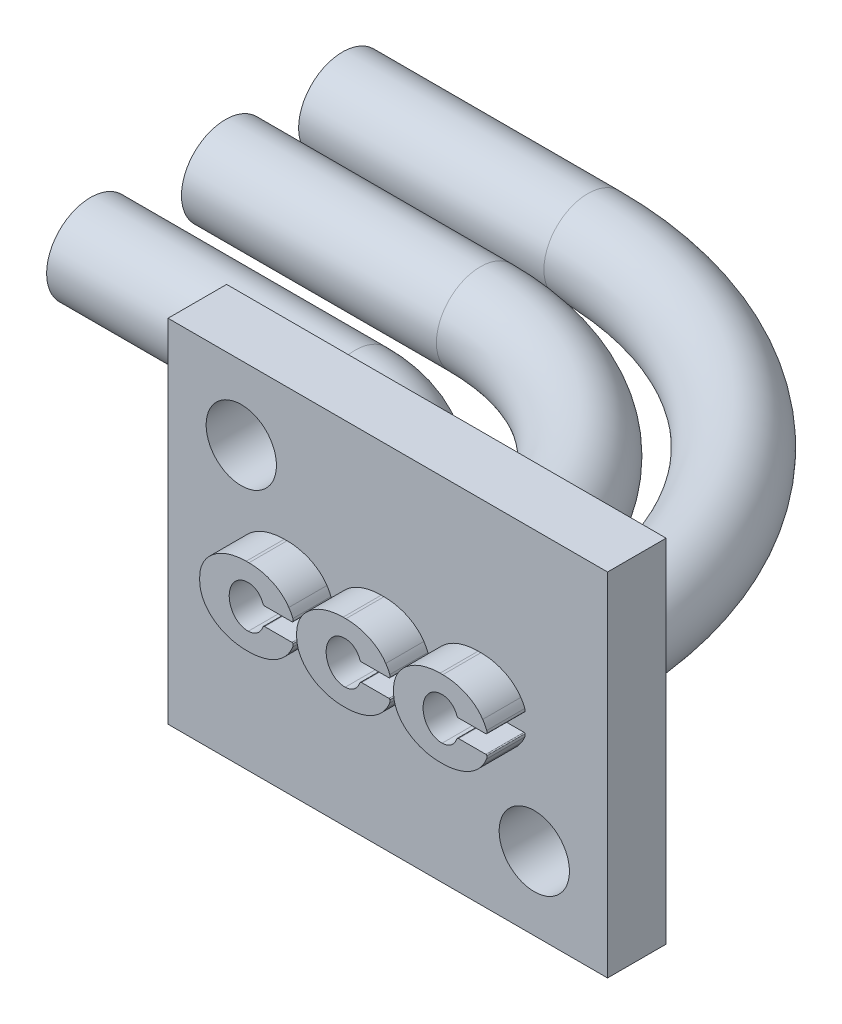
SolidWorks part; units mm, degrees
ref_plane "Front Plane" through (0, 0, 0) normal (0, 0, 1) x (1, 0, 0)
ref_plane "Top Plane" through (0, 0, 0) normal (0, 1, 0) x (1, 0, 0)
ref_plane "Right Plane" through (0, 0, 0) normal (1, 0, 0) x (0, 0, -1)
sketch "Sketch1" plane through (0, 0, 0) normal (0, 0, 1) x (1, 0, 0)
  line L1 (-7.5, 6) -> (7.5, 6)
  line L2 (-7.5, 6) -> (-7.5, -6)
  line L3 (-7.5, -6) -> (7.5, -6)
  line L4 (7.5, 6) -> (7.5, -6)
  line L5 (-7.5, 6) -> (7.5, -6) construction
  line L6 (-7.5, -6) -> (7.5, 6) construction
  point P0 (0, 0)
  dimension "D1" = 15
  dimension "D2" = 12
extrude "Boss-Extrude1" add sketch "Sketch1" along normal blind 2
sketch "Sketch2" plane through (0, 0, 2) normal (0, 0, 1) x (1, 0, 0)
  line L0 (0.4072, 0.4423) -> (1.3431, 0.4423)
  line L1 (-0.1301, 1.4531) -> (-0.2238, 1.4531)
  line L2 (-1.8094, 0.2019) -> (-1.8094, 0.0718)
  line L3 (-0.2238, -1.1794) -> (-0.1301, -1.1794)
  line L4 (1.3385, -0.1647) -> (0.4072, -0.1647)
  line L5 (-2.9011, 0.4423) -> (-1.9652, 0.4423)
  line L6 (-3.4384, 1.4531) -> (-3.5321, 1.4531)
  line L7 (-5.1177, 0.2019) -> (-5.1177, 0.0718)
  line L8 (-3.5321, -1.1794) -> (-3.4384, -1.1794)
  line L9 (-1.9698, -0.1647) -> (-2.9011, -0.1647)
  line L10 (3.7155, 0.4423) -> (4.6514, 0.4423)
  line L11 (3.1782, 1.4531) -> (3.0846, 1.4531)
  line L12 (1.4989, 0.2019) -> (1.4989, 0.0718)
  line L13 (3.0846, -1.1794) -> (3.1782, -1.1794)
  line L14 (4.6469, -0.1647) -> (3.7155, -0.1647)
  arc A0 (0.3456, 0.4859) -> (0.4072, 0.4423) centre (0.4072, 0.5078) ccw
  arc A1 (1.3431, 0.4423) -> (1.3723, 0.4672) centre (1.3386, 0.4772) ccw
  arc A2 (1.3723, 0.4672) -> (1.3681, 0.5547) centre (1.1917, 0.5024) ccw
  arc A3 (1.3681, 0.5547) -> (1.231, 0.812) centre (0.2861, 0.1431) ccw
  arc A4 (1.231, -0.5382) -> (1.3634, -0.2919) centre (0.2955, 0.1234) ccw
  arc A5 (1.3634, -0.2919) -> (1.3732, -0.1939) centre (1.1919, -0.2252) ccw
  arc A6 (1.3732, -0.1939) -> (1.3385, -0.1647) centre (1.3385, -0.1999) ccw
  arc A7 (0.4072, -0.1647) -> (0.3456, -0.2083) centre (0.4072, -0.2302) ccw
  arc A8 (-2.9627, 0.4859) -> (-2.9011, 0.4423) centre (-2.9011, 0.5078) ccw
  arc A9 (-1.9652, 0.4423) -> (-1.936, 0.4672) centre (-1.9697, 0.4772) ccw
  arc A10 (-1.936, 0.4672) -> (-1.9402, 0.5547) centre (-2.1166, 0.5024) ccw
  arc A11 (-1.9402, 0.5547) -> (-2.0773, 0.812) centre (-3.0222, 0.1431) ccw
  arc A12 (-2.0773, -0.5382) -> (-1.9449, -0.2919) centre (-3.0128, 0.1234) ccw
  arc A13 (-1.9449, -0.2919) -> (-1.9351, -0.1939) centre (-2.1164, -0.2252) ccw
  arc A14 (-1.9351, -0.1939) -> (-1.9698, -0.1647) centre (-1.9698, -0.1999) ccw
  arc A15 (-2.9011, -0.1647) -> (-2.9627, -0.2083) centre (-2.9011, -0.2302) ccw
  arc A16 (3.6539, 0.4859) -> (3.7155, 0.4423) centre (3.7155, 0.5078) ccw
  arc A17 (4.6514, 0.4423) -> (4.6806, 0.4672) centre (4.6469, 0.4772) ccw
  arc A18 (4.6806, 0.4672) -> (4.6764, 0.5547) centre (4.5, 0.5024) ccw
  arc A19 (4.6764, 0.5547) -> (4.5393, 0.812) centre (3.5944, 0.1431) ccw
  arc A20 (4.5393, -0.5382) -> (4.6717, -0.2919) centre (3.6038, 0.1234) ccw
  arc A21 (4.6717, -0.2919) -> (4.6815, -0.1939) centre (4.5002, -0.2252) ccw
  arc A22 (4.6815, -0.1939) -> (4.6469, -0.1647) centre (4.6469, -0.1999) ccw
  arc A23 (3.7155, -0.1647) -> (3.6539, -0.2083) centre (3.7155, -0.2302) ccw
  ellipse E0 centre (-0.1827, 0.137) end of major axis (-0.1791, -0.5801) minor radius 0.6209 (-0.2107, 0.8534) -> (-0.1509, -0.5792) ccw
  ellipse E1 centre (-0.2388, 0.137) end of major axis (0.0439, 0.8186) minor radius 0.6039 (0.3456, 0.4859) -> (-0.2107, 0.8534) ccw
  ellipse E2 centre (-0.2522, 0.1514) end of major axis (1.3906, 0.3966) minor radius 1.2925 (1.231, 0.812) -> (-0.1301, 1.4531) ccw
  ellipse E3 centre (-0.1614, 0.1527) end of major axis (-1.8063, 0.2821) minor radius 1.2979 (-0.2238, 1.4531) -> (-1.8094, 0.2019) ccw
  ellipse E4 centre (-0.1614, 0.121) end of major axis (1.4835, 0.2504) minor radius 1.2979 (-1.8094, 0.0718) -> (-0.2238, -1.1794) ccw
  ellipse E5 centre (-0.2522, 0.1223) end of major axis (-1.895, 0.3674) minor radius 1.2925 (-0.1301, -1.1794) -> (1.231, -0.5382) ccw
  ellipse E6 centre (-0.2388, 0.1406) end of major axis (0.0439, -0.541) minor radius 0.6039 (-0.1509, -0.5792) -> (0.3456, -0.2083) ccw
  ellipse E7 centre (-3.5471, 0.137) end of major axis (-3.2644, 0.8186) minor radius 0.6039 (-2.9627, 0.4859) -> (-3.519, 0.8534) ccw
  ellipse E8 centre (-3.5605, 0.1514) end of major axis (-1.9177, 0.3966) minor radius 1.2925 (-2.0773, 0.812) -> (-3.4384, 1.4531) ccw
  ellipse E9 centre (-3.4697, 0.1527) end of major axis (-5.1146, 0.2821) minor radius 1.2979 (-3.5321, 1.4531) -> (-5.1177, 0.2019) ccw
  ellipse E10 centre (-3.4697, 0.121) end of major axis (-1.8248, 0.2504) minor radius 1.2979 (-5.1177, 0.0718) -> (-3.5321, -1.1794) ccw
  ellipse E11 centre (-3.5605, 0.1223) end of major axis (-1.9177, -0.1229) minor radius 1.2925 (-3.4384, -1.1794) -> (-2.0773, -0.5382) ccw
  ellipse E12 centre (-3.5471, 0.1406) end of major axis (-3.8297, 0.8222) minor radius 0.6039 (-3.4592, -0.5792) -> (-2.9627, -0.2083) ccw
  ellipse E13 centre (-3.491, 0.137) end of major axis (-3.4946, 0.8541) minor radius 0.6209 (-3.519, 0.8534) -> (-3.4592, -0.5792) ccw
  ellipse E14 centre (3.1256, 0.137) end of major axis (3.1292, -0.5801) minor radius 0.6209 (3.0976, 0.8534) -> (3.1574, -0.5792) ccw
  ellipse E15 centre (3.0695, 0.137) end of major axis (3.3522, 0.8186) minor radius 0.6039 (3.6539, 0.4859) -> (3.0976, 0.8534) ccw
  ellipse E16 centre (3.0561, 0.1514) end of major axis (4.6989, 0.3966) minor radius 1.2925 (4.5393, 0.812) -> (3.1782, 1.4531) ccw
  ellipse E17 centre (3.1469, 0.1527) end of major axis (1.502, 0.2821) minor radius 1.2979 (3.0846, 1.4531) -> (1.4989, 0.2019) ccw
  ellipse E18 centre (3.1469, 0.121) end of major axis (4.7918, 0.2504) minor radius 1.2979 (1.4989, 0.0718) -> (3.0846, -1.1794) ccw
  ellipse E19 centre (3.0561, 0.1223) end of major axis (1.4133, 0.3674) minor radius 1.2925 (3.1782, -1.1794) -> (4.5393, -0.5382) ccw
  ellipse E20 centre (3.0695, 0.1406) end of major axis (3.3522, -0.541) minor radius 0.6039 (3.1574, -0.5792) -> (3.6539, -0.2083) ccw
extrude "Boss-Extrude2" add sketch "Sketch2" along normal blind 2
sketch "Sketch3" plane through (0, 0, 0) normal (0, 1, 0) x (1, 0, 0)
  line L0 (7.5, 0) -> (-7.5, 0) construction
  line L1 (2.7287, 0) -> (4.2287, 0)
  line L2 (2.7287, 0) -> (2.7287, 12.6)
  line L3 (-3.864, -2) -> (-3.864, 5.3789) construction
  line L4 (4.2287, 0) -> (4.2287, 14.1)
  line L5 (-4.614, 0) -> (-3.114, 0)
  line L6 (-4.614, 0) -> (-4.614, 4)
  line L7 (-0.1926, -2) -> (-0.1926, 4.6797) construction
  line L8 (-3.114, 0) -> (-3.114, 4)
  line L9 (-3.114, 4) -> (-4.614, 4)
  line L10 (-0.9426, 0) -> (0.5574, 0)
  line L13 (-0.9426, 0) -> (-0.9426, 8.6)
  line L14 (3.4787, -2) -> (3.4787, 2.787) construction
  line L15 (0.5574, 0) -> (0.5574, 10.1)
  line L16 (0.5574, 10.1) -> (-2.6426, 10.1)
  line L17 (-2.4226, 14.1) -> (4.2287, 14.1)
  line L18 (-0.9426, 8.6) -> (-2.6426, 8.6)
  line L19 (-2.6426, 10.1) -> (-2.6426, 8.6)
  line L20 (-2.4226, 14.1) -> (-2.4226, 12.6)
  line L21 (-2.4226, 12.6) -> (2.7287, 12.6)
  dimension "D1" = 1.5
  dimension "D2" = 4
  dimension "D3" = 1.5
  dimension "D4" = 1.5
  dimension "D5" = 4.6
  dimension "D6" = 1.5
  dimension "D7" = 2.5
  dimension "D8" = 1.5
  dimension "D9" = 1.7
  dimension "D10" = 3.4787
  dimension "D11" = 0.1926
  dimension "D12" = 3.864
extrude "Boss-Extrude3" add sketch "Sketch3" along normal mid plane 4
sketch "Sketch4" [suppressed] plane through (0, 2, 0) normal (0, 1, 0) x (1, 0, 0)
  line L1 (-2.4226, 10.1) -> (-2.4226, 8.6) construction
  line L2 (-2.894, 4) -> (-11.894, 4)
  line L3 (-2.894, 4) -> (-2.894, 5.5)
  line L4 (-2.894, 5.5) -> (-11.894, 5.5)
  line L5 (-11.894, 4) -> (-11.894, 5.5)
  dimension "D1" = 9
extrude "Boss-Extrude4" [suppressed] add sketch "Sketch4" against normal up to surface (4 mm away)
sketch "Sketch5" [suppressed] plane through (-2.4226, 0, 0) normal (-1, 0, 0) x (0, 0, 1)
  line L4 (-10.1, -2) -> (-8.6, -2)
  line L5 (-8.6, -2) -> (-8.6, 2)
  line L6 (-8.6, 2) -> (-10.1, 2)
  line L7 (-10.1, 2) -> (-10.1, -2)
  line L8 (-10.1, -2) -> (-8.6, -2)
  line L9 (-8.6, -2) -> (-8.6, 2)
  line L10 (-8.6, 2) -> (-10.1, 2)
  line L11 (-10.1, 2) -> (-10.1, -2)
  line L12 (-14.1, -2) -> (-12.6, -2)
  line L13 (-12.6, -2) -> (-12.6, 2)
  line L14 (-12.6, 2) -> (-14.1, 2)
  line L15 (-14.1, 2) -> (-14.1, -2)
  line L16 (-14.1, -2) -> (-12.6, -2)
  line L17 (-12.6, -2) -> (-12.6, 2)
  line L18 (-12.6, 2) -> (-14.1, 2)
  line L19 (-14.1, 2) -> (-14.1, -2)
  dimension "D1" = 0
  dimension "D2" = 0
extrude "Boss-Extrude5" [suppressed] add sketch "Sketch5" along normal up to surface (9.4714 mm away)
sketch "Sketch6" plane through (0, 0, 0) normal (0, 0, -1) x (-1, 0, 0)
  line L0 (-4.2287, 0) -> (-2.7287, 0) construction
  line L1 (-4.2287, 2) -> (-4.2287, -2) construction
  line L2 (-2.7287, 2) -> (-2.7287, -2) construction
  line L3 (-0.5574, 0) -> (0.9426, 0) construction
  line L4 (-0.5574, 2) -> (-0.5574, -2) construction
  line L5 (0.9426, 2) -> (0.9426, -2) construction
  line L6 (3.114, 0) -> (4.614, 0) construction
  line L7 (3.114, 2) -> (3.114, -2) construction
  line L8 (4.614, 2) -> (4.614, -2) construction
  circle A0 centre (-3.4787, 0) radius 1.5
  dimension "D1" = 3
sketch "Sketch7" plane through (0, 0, 0) normal (0, 0, -1) x (-1, 0, 0)
  circle A0 centre (0, 0) radius 1.5
  dimension "D1" = 3
sketch "Sketch8" plane through (0, 0, 0) normal (0, 0, -1) x (-1, 0, 0)
  line L0 (3.114, 0) -> (4.614, 0) construction
  circle A0 centre (3.864, 0) radius 1.5
  dimension "D1" = 3
sketch "Sketch9" plane through (0, 0, 0) normal (0, 1, 0) x (1, 0, 0)
  line L0 (-3.864, 0) -> (-3.864, 0.75)
  line L1 (-3.114, 0) -> (-4.614, 0) construction
  line L2 (-7.864, 4.75) -> (-16.894, 4.75)
  arc A0 (-3.864, 0.75) -> (-7.864, 4.75) centre (-7.864, 0.75) ccw
  point P7 (-3.864, 4.75)
  dimension "D3" = 4
  dimension "D1" = 4.75
  dimension "D2" = 13.03
sketch "Sketch10" plane through (0, 0, 0) normal (0, 1, 0) x (1, 0, 0)
  line L0 (-0.1926, 0) -> (-0.1926, 1.16)
  line L1 (0.5574, 0) -> (-0.9426, 0) construction
  line L2 (-8.1926, 9.16) -> (-16.894, 9.16)
  arc A0 (-0.1926, 1.16) -> (-8.1926, 9.16) centre (-8.1926, 1.16) ccw
  point P7 (-0.1926, 9.16)
  dimension "D3" = 8
  dimension "D1" = 16.7014
  dimension "D2" = 9.16
sketch "Sketch11" plane through (0, 0, 0) normal (0, 1, 0) x (1, 0, 0)
  line L0 (3.4787, 0) -> (3.4787, 1.35)
  line L1 (4.2287, 0) -> (2.7287, 0) construction
  line L2 (-8.5213, 13.35) -> (-16.894, 13.35)
  arc A0 (3.4787, 1.35) -> (-8.5213, 13.35) centre (-8.5213, 1.35) ccw
  point P7 (3.4787, 13.35)
  dimension "D3" = 12
  dimension "D1" = 13.35
  dimension "D2" = 20.3728
sketch "Sketch12" plane through (7.5, 0, 0) normal (1, 0, 0) x (0, 0, -1)
  line L1 (0, -6) -> (14.1, -6)
  line L2 (0, -6) -> (0, 2)
  line L3 (0, 2) -> (14.1, 2)
  line L4 (14.1, -6) -> (14.1, 2)
extrude "Cut-Extrude1" cut sketch "Sketch12" against normal through all
sweep "Sweep1" add profiles "Sketch8" path "Sketch9"
sweep "Sweep2" add profiles "Sketch7" path "Sketch10"
sweep "Sweep3" add profiles "Sketch6" path "Sketch11"
sketch "Sketch13" plane through (0, 0, 0) normal (0, 0, -1) x (-1, 0, 0)
  line L0 (-7.5, 6) -> (7.5, 6) construction
  line L1 (7.5, 6) -> (7.5, -6) construction
  line L2 (7.5, -6) -> (-7.5, -6) construction
  line L3 (-7.5, -6) -> (-7.5, 6) construction
  circle A0 centre (-5, -3.5) radius 1.2
  circle A1 centre (5, 3.5) radius 1.2
  dimension "D5" = 2.4
  dimension "D1" = 2.5
  dimension "D2" = 2.5
  dimension "D3" = 2.5
  dimension "D4" = 2.5
extrude "Cut-Extrude2" cut sketch "Sketch13" against normal through all
sketch "Sketch15" plane through (0, 0, 4) normal (0, 0, 1) x (1, 0, 0)
  line L0 (0.4072, 0.4423) -> (1.3431, 0.4423) construction
  line L1 (-0.1301, 1.4531) -> (-0.2238, 1.4531) construction
  line L2 (-1.8094, 0.2019) -> (-1.8094, 0.0718) construction
  line L3 (-0.2238, -1.1794) -> (-0.1301, -1.1794) construction
  line L4 (1.3385, -0.1647) -> (0.4072, -0.1647) construction
  line L5 (-2.9011, 0.4423) -> (-1.9652, 0.4423)
  line L6 (-3.4384, 1.4531) -> (-3.5321, 1.4531)
  line L7 (-5.1177, 0.2019) -> (-5.1177, 0.0718)
  line L8 (-3.5321, -1.1794) -> (-3.4384, -1.1794)
  line L9 (-1.9698, -0.1647) -> (-2.9011, -0.1647)
  line L10 (-2.9011, 0.4423) -> (-1.9652, 0.4423)
  line L11 (-3.4384, 1.4531) -> (-3.5321, 1.4531)
  line L12 (-5.1177, 0.2019) -> (-5.1177, 0.0718)
  line L13 (-3.5321, -1.1794) -> (-3.4384, -1.1794)
  line L14 (-1.9698, -0.1647) -> (-2.9011, -0.1647)
  line L15 (3.7155, 0.4423) -> (4.6514, 0.4423) construction
  line L16 (3.1782, 1.4531) -> (3.0846, 1.4531) construction
  line L17 (1.4989, 0.2019) -> (1.4989, 0.0718) construction
  line L18 (3.0846, -1.1794) -> (3.1782, -1.1794) construction
  line L19 (4.6469, -0.1647) -> (3.7155, -0.1647) construction
  line L20 (0.4072, 0.4423) -> (1.3431, 0.4423)
  line L21 (-0.1301, 1.4531) -> (-0.2238, 1.4531)
  line L22 (-1.8094, 0.2019) -> (-1.8094, 0.0718)
  line L23 (-0.2238, -1.1794) -> (-0.1301, -1.1794)
  line L24 (1.3385, -0.1647) -> (0.4072, -0.1647)
  line L25 (3.7155, 0.4423) -> (4.6514, 0.4423)
  line L26 (3.1782, 1.4531) -> (3.0846, 1.4531)
  line L27 (1.4989, 0.2019) -> (1.4989, 0.0718)
  line L28 (3.0846, -1.1794) -> (3.1782, -1.1794)
  line L29 (4.6469, -0.1647) -> (3.7155, -0.1647)
  arc A0 (0.3456, 0.4859) -> (0.4072, 0.4423) centre (0.4072, 0.5078) ccw construction
  arc A1 (1.3431, 0.4423) -> (1.3723, 0.4672) centre (1.3386, 0.4772) ccw construction
  arc A2 (1.3723, 0.4672) -> (1.3681, 0.5547) centre (1.1917, 0.5024) ccw construction
  arc A3 (1.3681, 0.5547) -> (1.231, 0.812) centre (0.2861, 0.1431) ccw construction
  arc A4 (1.231, -0.5382) -> (1.3634, -0.2919) centre (0.2955, 0.1234) ccw construction
  arc A5 (1.3634, -0.2919) -> (1.3732, -0.1939) centre (1.1919, -0.2252) ccw construction
  arc A6 (1.3732, -0.1939) -> (1.3385, -0.1647) centre (1.3385, -0.1999) ccw construction
  arc A7 (0.4072, -0.1647) -> (0.3456, -0.2083) centre (0.4072, -0.2302) ccw construction
  arc A8 (-2.9627, 0.4859) -> (-2.9011, 0.4423) centre (-2.9011, 0.5078) ccw
  arc A9 (-1.9652, 0.4423) -> (-1.936, 0.4672) centre (-1.9697, 0.4772) ccw
  arc A10 (-1.936, 0.4672) -> (-1.9402, 0.5547) centre (-2.1166, 0.5024) ccw
  arc A11 (-1.9402, 0.5547) -> (-2.0773, 0.812) centre (-3.0222, 0.1431) ccw
  arc A12 (-2.0773, -0.5382) -> (-1.9449, -0.2919) centre (-3.0128, 0.1234) ccw
  arc A13 (-1.9449, -0.2919) -> (-1.9351, -0.1939) centre (-2.1164, -0.2252) ccw
  arc A14 (-1.9351, -0.1939) -> (-1.9698, -0.1647) centre (-1.9698, -0.1999) ccw
  arc A15 (-2.9011, -0.1647) -> (-2.9627, -0.2083) centre (-2.9011, -0.2302) ccw
  arc A16 (-2.9627, 0.4859) -> (-2.9011, 0.4423) centre (-2.9011, 0.5078) ccw
  arc A17 (-1.9652, 0.4423) -> (-1.936, 0.4672) centre (-1.9697, 0.4772) ccw
  arc A18 (-1.936, 0.4672) -> (-1.9402, 0.5547) centre (-2.1166, 0.5024) ccw
  arc A19 (-1.9402, 0.5547) -> (-2.0773, 0.812) centre (-3.0222, 0.1431) ccw
  arc A20 (-2.0773, -0.5382) -> (-1.9449, -0.2919) centre (-3.0128, 0.1234) ccw
  arc A21 (-1.9449, -0.2919) -> (-1.9351, -0.1939) centre (-2.1164, -0.2252) ccw
  arc A22 (-1.9351, -0.1939) -> (-1.9698, -0.1647) centre (-1.9698, -0.1999) ccw
  arc A23 (-2.9011, -0.1647) -> (-2.9627, -0.2083) centre (-2.9011, -0.2302) ccw
  arc A24 (3.6539, 0.4859) -> (3.7155, 0.4423) centre (3.7155, 0.5078) ccw construction
  arc A25 (4.6514, 0.4423) -> (4.6806, 0.4672) centre (4.6469, 0.4772) ccw construction
  arc A26 (4.6806, 0.4672) -> (4.6764, 0.5547) centre (4.5, 0.5024) ccw construction
  arc A27 (4.6764, 0.5547) -> (4.5393, 0.812) centre (3.5944, 0.1431) ccw construction
  arc A28 (4.5393, -0.5382) -> (4.6717, -0.2919) centre (3.6038, 0.1234) ccw construction
  arc A29 (4.6717, -0.2919) -> (4.6815, -0.1939) centre (4.5002, -0.2252) ccw construction
  arc A30 (4.6815, -0.1939) -> (4.6469, -0.1647) centre (4.6469, -0.1999) ccw construction
  arc A31 (3.7155, -0.1647) -> (3.6539, -0.2083) centre (3.7155, -0.2302) ccw construction
  arc A32 (0.3456, 0.4859) -> (0.4072, 0.4423) centre (0.4072, 0.5078) ccw
  arc A33 (1.3431, 0.4423) -> (1.3723, 0.4672) centre (1.3386, 0.4772) ccw
  arc A34 (1.3723, 0.4672) -> (1.3681, 0.5547) centre (1.1917, 0.5024) ccw
  arc A35 (1.3681, 0.5547) -> (1.231, 0.812) centre (0.2861, 0.1431) ccw
  arc A36 (1.231, -0.5382) -> (1.3634, -0.2919) centre (0.2955, 0.1234) ccw
  arc A37 (1.3634, -0.2919) -> (1.3732, -0.1939) centre (1.1919, -0.2252) ccw
  arc A38 (1.3732, -0.1939) -> (1.3385, -0.1647) centre (1.3385, -0.1999) ccw
  arc A39 (0.4072, -0.1647) -> (0.3456, -0.2083) centre (0.4072, -0.2302) ccw
  arc A40 (3.6539, 0.4859) -> (3.7155, 0.4423) centre (3.7155, 0.5078) ccw
  arc A41 (4.6514, 0.4423) -> (4.6806, 0.4672) centre (4.6469, 0.4772) ccw
  arc A42 (4.6806, 0.4672) -> (4.6764, 0.5547) centre (4.5, 0.5024) ccw
  arc A43 (4.6764, 0.5547) -> (4.5393, 0.812) centre (3.5944, 0.1431) ccw
  arc A44 (4.5393, -0.5382) -> (4.6717, -0.2919) centre (3.6038, 0.1234) ccw
  arc A45 (4.6717, -0.2919) -> (4.6815, -0.1939) centre (4.5002, -0.2252) ccw
  arc A46 (4.6815, -0.1939) -> (4.6469, -0.1647) centre (4.6469, -0.1999) ccw
  arc A47 (3.7155, -0.1647) -> (3.6539, -0.2083) centre (3.7155, -0.2302) ccw
  ellipse E0 centre (-0.2388, 0.137) end of major axis (-0.5214, -0.5446) minor radius 0.6039 (0.3456, 0.4859) -> (-0.2107, 0.8534) ccw construction
  ellipse E1 centre (-0.2522, 0.1514) end of major axis (1.3906, 0.3966) minor radius 1.2925 (1.231, 0.812) -> (-0.1301, 1.4531) ccw construction
  ellipse E2 centre (-0.1614, 0.1527) end of major axis (-1.8063, 0.2821) minor radius 1.2979 (-0.2238, 1.4531) -> (-1.8094, 0.2019) ccw construction
  ellipse E3 centre (-0.1614, 0.121) end of major axis (1.4835, 0.2504) minor radius 1.2979 (-1.8094, 0.0718) -> (-0.2238, -1.1794) ccw construction
  ellipse E4 centre (-0.2522, 0.1223) end of major axis (-1.895, 0.3674) minor radius 1.2925 (-0.1301, -1.1794) -> (1.231, -0.5382) ccw construction
  ellipse E5 centre (-0.2388, 0.1406) end of major axis (0.0439, -0.541) minor radius 0.6039 (-0.1509, -0.5792) -> (0.3456, -0.2083) ccw construction
  ellipse E6 centre (-0.1827, 0.137) end of major axis (-0.1791, -0.5801) minor radius 0.6209 (-0.2107, 0.8534) -> (-0.1509, -0.5792) ccw construction
  ellipse E7 centre (-3.5471, 0.137) end of major axis (-3.8297, -0.5446) minor radius 0.6039 (-2.9627, 0.4859) -> (-3.519, 0.8534) ccw
  ellipse E8 centre (-3.5605, 0.1514) end of major axis (-5.2033, -0.0937) minor radius 1.2925 (-2.0773, 0.812) -> (-3.4384, 1.4531) ccw
  ellipse E9 centre (-3.4697, 0.1527) end of major axis (-5.1146, 0.2821) minor radius 1.2979 (-3.5321, 1.4531) -> (-5.1177, 0.2019) ccw
  ellipse E10 centre (-3.4697, 0.121) end of major axis (-1.8248, 0.2504) minor radius 1.2979 (-5.1177, 0.0718) -> (-3.5321, -1.1794) ccw
  ellipse E11 centre (-3.5605, 0.1223) end of major axis (-1.9177, -0.1229) minor radius 1.2925 (-3.4384, -1.1794) -> (-2.0773, -0.5382) ccw
  ellipse E12 centre (-3.5471, 0.1406) end of major axis (-3.2644, -0.541) minor radius 0.6039 (-3.4592, -0.5792) -> (-2.9627, -0.2083) ccw
  ellipse E13 centre (-3.491, 0.137) end of major axis (-3.4874, -0.5801) minor radius 0.6209 (-3.519, 0.8534) -> (-3.4592, -0.5792) ccw
  ellipse E14 centre (-3.5471, 0.137) end of major axis (-3.8297, -0.5446) minor radius 0.6039 (-2.9627, 0.4859) -> (-3.519, 0.8534) ccw
  ellipse E15 centre (-3.5605, 0.1514) end of major axis (-5.2033, -0.0937) minor radius 1.2925 (-2.0773, 0.812) -> (-3.4384, 1.4531) ccw
  ellipse E16 centre (-3.4697, 0.1527) end of major axis (-5.1146, 0.2821) minor radius 1.2979 (-3.5321, 1.4531) -> (-5.1177, 0.2019) ccw
  ellipse E17 centre (-3.4697, 0.121) end of major axis (-1.8248, 0.2504) minor radius 1.2979 (-5.1177, 0.0718) -> (-3.5321, -1.1794) ccw
  ellipse E18 centre (-3.5605, 0.1223) end of major axis (-5.2033, 0.3674) minor radius 1.2925 (-3.4384, -1.1794) -> (-2.0773, -0.5382) ccw
  ellipse E19 centre (-3.5471, 0.1406) end of major axis (-3.2644, -0.541) minor radius 0.6039 (-3.4592, -0.5792) -> (-2.9627, -0.2083) ccw
  ellipse E20 centre (-3.491, 0.137) end of major axis (-3.4874, -0.5801) minor radius 0.6209 (-3.519, 0.8534) -> (-3.4592, -0.5792) ccw
  ellipse E21 centre (3.0695, 0.137) end of major axis (2.7869, -0.5446) minor radius 0.6039 (3.6539, 0.4859) -> (3.0976, 0.8534) ccw construction
  ellipse E22 centre (3.0561, 0.1514) end of major axis (1.4133, -0.0937) minor radius 1.2925 (4.5393, 0.812) -> (3.1782, 1.4531) ccw construction
  ellipse E23 centre (3.1469, 0.1527) end of major axis (4.7918, 0.0234) minor radius 1.2979 (3.0846, 1.4531) -> (1.4989, 0.2019) ccw construction
  ellipse E24 centre (3.1469, 0.121) end of major axis (4.7918, 0.2504) minor radius 1.2979 (1.4989, 0.0718) -> (3.0846, -1.1794) ccw construction
  ellipse E25 centre (3.0561, 0.1223) end of major axis (1.4133, 0.3674) minor radius 1.2925 (3.1782, -1.1794) -> (4.5393, -0.5382) ccw construction
  ellipse E26 centre (3.0695, 0.1406) end of major axis (3.3522, -0.541) minor radius 0.6039 (3.1574, -0.5792) -> (3.6539, -0.2083) ccw construction
  ellipse E27 centre (3.1256, 0.137) end of major axis (3.1292, -0.5801) minor radius 0.6209 (3.0976, 0.8534) -> (3.1574, -0.5792) ccw construction
  ellipse E28 centre (-0.2388, 0.137) end of major axis (-0.5214, -0.5446) minor radius 0.6039 (0.3456, 0.4859) -> (-0.2107, 0.8534) ccw
  ellipse E29 centre (-0.2522, 0.1514) end of major axis (1.3906, 0.3966) minor radius 1.2925 (1.231, 0.812) -> (-0.1301, 1.4531) ccw
  ellipse E30 centre (-0.1614, 0.1527) end of major axis (-1.8063, 0.2821) minor radius 1.2979 (-0.2238, 1.4531) -> (-1.8094, 0.2019) ccw
  ellipse E31 centre (-0.1614, 0.121) end of major axis (1.4835, 0.2504) minor radius 1.2979 (-1.8094, 0.0718) -> (-0.2238, -1.1794) ccw
  ellipse E32 centre (-0.2522, 0.1223) end of major axis (-1.895, 0.3674) minor radius 1.2925 (-0.1301, -1.1794) -> (1.231, -0.5382) ccw
  ellipse E33 centre (-0.2388, 0.1406) end of major axis (0.0439, -0.541) minor radius 0.6039 (-0.1509, -0.5792) -> (0.3456, -0.2083) ccw
  ellipse E34 centre (-0.1827, 0.137) end of major axis (-0.1791, -0.5801) minor radius 0.6209 (-0.2107, 0.8534) -> (-0.1509, -0.5792) ccw
  ellipse E35 centre (3.0695, 0.137) end of major axis (2.7869, -0.5446) minor radius 0.6039 (3.6539, 0.4859) -> (3.0976, 0.8534) ccw
  ellipse E36 centre (3.0561, 0.1514) end of major axis (4.6989, 0.3966) minor radius 1.2925 (4.5393, 0.812) -> (3.1782, 1.4531) ccw
  ellipse E37 centre (3.1469, 0.1527) end of major axis (4.7918, 0.0234) minor radius 1.2979 (3.0846, 1.4531) -> (1.4989, 0.2019) ccw
  ellipse E38 centre (3.1469, 0.121) end of major axis (4.7918, 0.2504) minor radius 1.2979 (1.4989, 0.0718) -> (3.0846, -1.1794) ccw
  ellipse E39 centre (3.0561, 0.1223) end of major axis (1.4133, 0.3674) minor radius 1.2925 (3.1782, -1.1794) -> (4.5393, -0.5382) ccw
  ellipse E40 centre (3.0695, 0.1406) end of major axis (3.3522, -0.541) minor radius 0.6039 (3.1574, -0.5792) -> (3.6539, -0.2083) ccw
  ellipse E41 centre (3.1256, 0.137) end of major axis (3.1292, -0.5801) minor radius 0.6209 (3.0976, 0.8534) -> (3.1574, -0.5792) ccw
  dimension "D1" = 0
extrude "Cut-Extrude3" cut sketch "Sketch15" against normal blind 0.7
